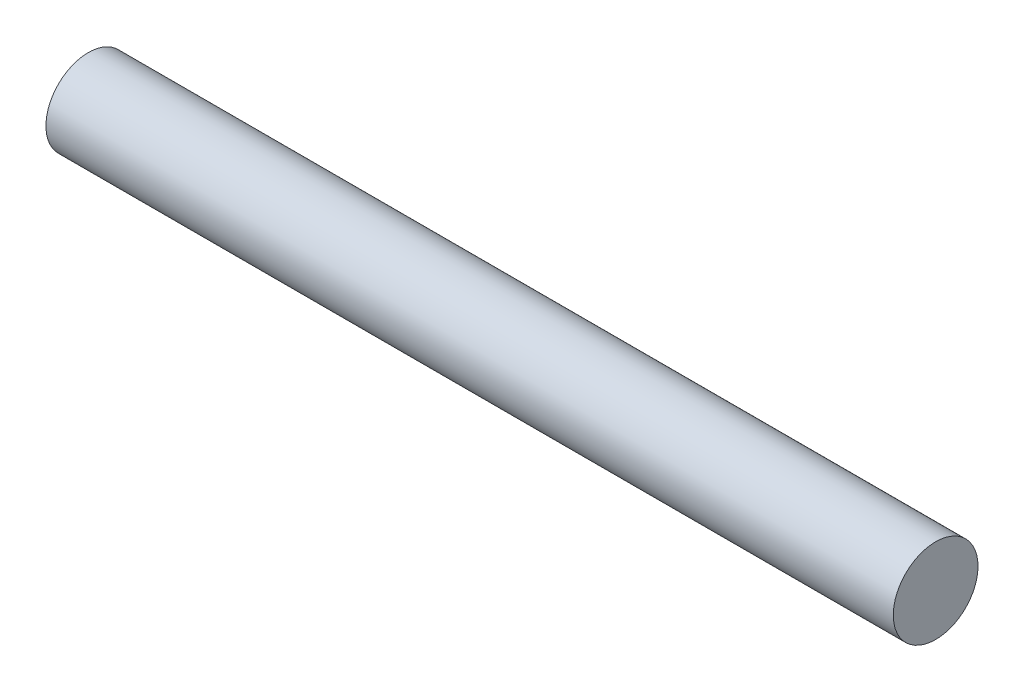
SolidWorks part; units mm, degrees
ref_plane "Front Plane" through (0, 0, 0) normal (0, 0, 1) x (1, 0, 0)
ref_plane "Top Plane" through (0, 0, 0) normal (0, 1, 0) x (1, 0, 0)
ref_plane "Right Plane" through (0, 0, 0) normal (1, 0, 0) x (0, 0, -1)
sketch "Sketch1" plane through (0, 0, 0) normal (1, 0, 0) x (0, 0, -1)
  circle A0 centre (0, 0) radius 5
  dimension "D1" = 10
extrude "Boss-Extrude1" add sketch "Sketch1" along normal blind 100
